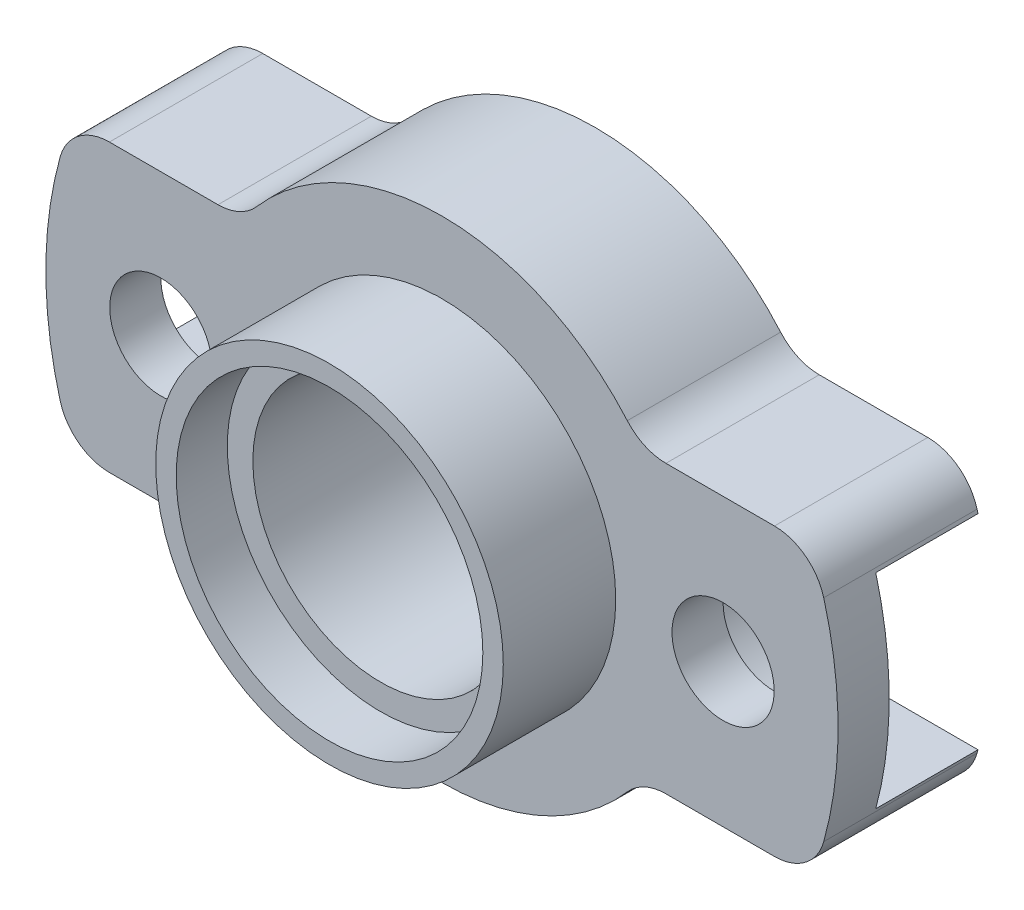
SolidWorks part; units mm, degrees
ref_plane "前视基准面" through (0, 0, 0) normal (0, 0, 1) x (1, 0, 0)
ref_plane "上视基准面" through (0, 0, 0) normal (0, 1, 0) x (1, 0, 0)
ref_plane "右视基准面" through (0, 0, 0) normal (1, 0, 0) x (0, 0, -1)
other "Configuration Table"
sketch "草图1" plane through (0, 0, 0) normal (0, 0, 1) x (1, 0, 0)
  line L0 (-6.5056, 2.8) -> (-4.3818, 2.8)
  line L1 (55, 0) -> (-55, 0) construction
  line L2 (-6.5056, -2.8) -> (-4.3818, -2.8)
  line L3 (0, -55) -> (0, 55) construction
  line L4 (6.5056, -2.8) -> (4.3818, -2.8)
  line L5 (6.5056, 2.8) -> (4.3818, 2.8)
  arc A0 (-3.6263, -3.1448) -> (3.6263, -3.1448) centre (0, 0) ccw
  arc A1 (-7.4694, 2.0667) -> (-7.4694, -2.0667) centre (0, 0) ccw
  circle A2 centre (0, 0) radius 2.5
  arc A3 (7.4694, -2.0667) -> (7.4694, 2.0667) centre (0, 0) ccw
  arc A4 (3.6263, 3.1448) -> (-3.6263, 3.1448) centre (0, 0) ccw
  arc A5 (6.5056, -2.8) -> (7.4694, -2.0667) centre (6.5056, -1.8) ccw
  arc A6 (6.5056, 2.8) -> (7.4694, 2.0667) centre (6.5056, 1.8) cw
  arc A7 (4.3818, 2.8) -> (3.6263, 3.1448) centre (4.3818, 3.8) cw
  arc A8 (-4.3818, -2.8) -> (-3.6263, -3.1448) centre (-4.3818, -3.8) cw
  arc A9 (4.3818, -2.8) -> (3.6263, -3.1448) centre (4.3818, -3.8) ccw
  arc A10 (-6.5056, -2.8) -> (-7.4694, -2.0667) centre (-6.5056, -1.8) cw
  arc A11 (-6.5056, 2.8) -> (-7.4694, 2.0667) centre (-6.5056, 1.8) ccw
  arc A12 (-4.3818, 2.8) -> (-3.6263, 3.1448) centre (-4.3818, 3.8) ccw
  circle A13 centre (-5.5, 0) radius 1
  circle A14 centre (5.5, 0) radius 1
  point P17 (7.2265, -2.8)
  point P20 (7.2265, 2.8)
  point P23 (3.8987, 2.8)
  point P26 (-3.8987, -2.8)
  point P29 (3.8987, -2.8)
  point P32 (-7.2265, -2.8)
  point P35 (-7.2265, 2.8)
  point P38 (-3.8987, 2.8)
  dimension "D1" = 9.6
  dimension "D2" = 5
  dimension "D4" = 15.5
  dimension "D5" = 1
  dimension "D6" = 2
  dimension "D7" = 5.5
  dimension "D3" = 2.8
extrude "凸台-拉伸1" add sketch "草图1" along normal blind 3
sketch "草图2" plane through (0, 0, 3) normal (0, 0, 1) x (1, 0, 0)
  circle A0 centre (0, 0) radius 2.5
  circle A1 centre (0, 0) radius 3.4
  dimension "D1" = 6.8
  dimension "D2" = 5
extrude "凸台-拉伸2" add sketch "草图2" along normal blind 2.2
sketch "草图4" plane through (0, 0, 0) normal (0, 0, -1) x (-1, 0, 0)
  line L0 (-5.5, 2) -> (-7.4875, 2)
  line L1 (-5.5, -2) -> (-7.4875, -2)
  line L2 (0, 2.86) -> (0, -2.86) construction
  line L3 (5.5, -2) -> (7.4875, -2)
  line L4 (5.5, 2) -> (7.4875, 2)
  arc A0 (-5.5, -2) -> (-5.5, 2) centre (-5.5, 0) ccw
  arc A2 (-7.4694, 2.0667) -> (-7.4694, -2.0667) centre (0, 0) ccw construction
  arc A3 (-7.4875, 2) -> (-7.4875, -2) centre (0, 0) ccw
  arc A4 (7.4875, 2) -> (7.4875, -2) centre (0, 0) cw
  arc A5 (5.5, -2) -> (5.5, 2) centre (5.5, 0) cw
  dimension "D1" = 4
extrude "切除-拉伸1" cut sketch "草图4" against normal blind 2
sketch "草图5" plane through (0, 0, 5.2) normal (0, 0, 1) x (1, 0, 0)
  circle A0 centre (0, 0) radius 3
  dimension "D1" = 6
extrude "切除-拉伸2" cut sketch "草图5" against normal blind 1
